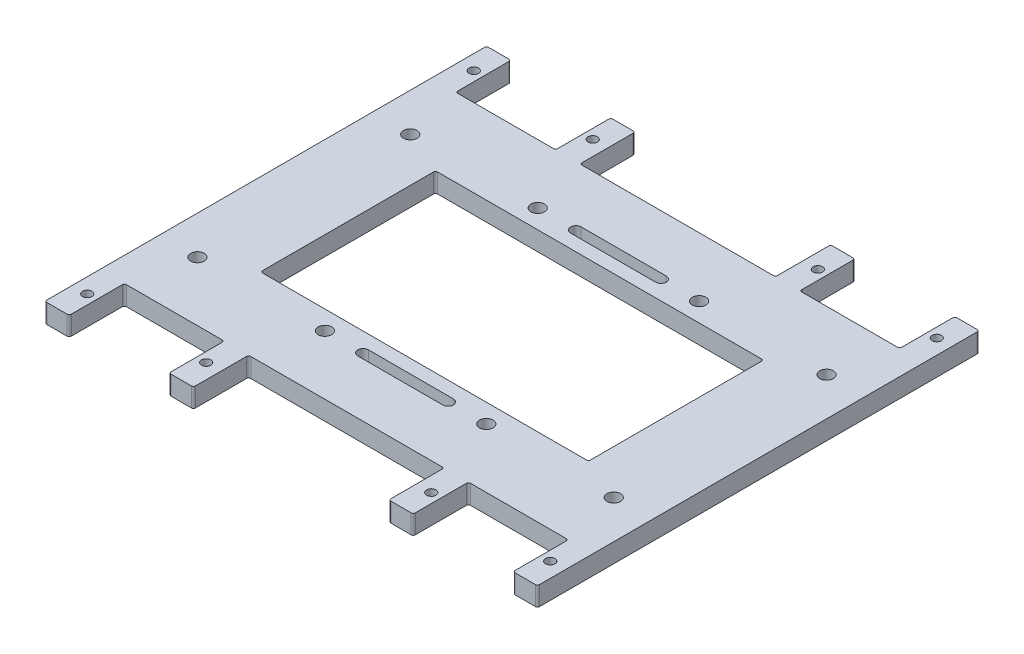
SolidWorks part; units mm, degrees
ref_plane "前视基准面" through (0, 0, 0) normal (0, 0, 1) x (1, 0, 0)
ref_plane "上视基准面" through (0, 0, 0) normal (0, 1, 0) x (1, 0, 0)
ref_plane "右视基准面" through (0, 0, 0) normal (1, 0, 0) x (0, 0, -1)
other "Configuration Table"
sketch "草图1" plane through (0, 0, 0) normal (0, 1, 0) x (1, 0, 0)
  line L0 (-58, -39) -> (-58, -52)
  line L2 (-58, 39) -> (-58, -39)
  line L4 (58, 39) -> (58, -39)
  line L5 (-58, 39) -> (58, -39) construction
  line L6 (-58, -39) -> (58, 39) construction
  line L15 (-78.7463, 0) -> (58.6748, 0) construction
  line L50 (-58, -52) -> (-52.25, -52)
  line L53 (-52.25, -52) -> (-52.25, -39)
  line L54 (-52.25, -39) -> (-28.75, -39)
  line L55 (-28.75, -39) -> (-28.75, -52)
  line L56 (-28.75, -52) -> (-23, -52)
  line L57 (-23, -52) -> (-23, -39)
  line L58 (-23, -39) -> (23, -39)
  line L59 (0, -1000) -> (0, 49000) construction
  line L60 (23, -52) -> (23, -39)
  line L61 (28.75, -52) -> (23, -52)
  line L62 (28.75, -39) -> (28.75, -52)
  line L63 (52.25, -39) -> (28.75, -39)
  line L64 (52.25, -52) -> (52.25, -39)
  line L65 (58, -52) -> (52.25, -52)
  line L66 (58, -39) -> (58, -52)
  line L67 (52.25, 39) -> (28.75, 39)
  line L68 (-23, 39) -> (23, 39)
  line L69 (-52.25, 39) -> (-28.75, 39)
  line L70 (0, 1000) -> (0, -49000) construction
  line L71 (58, 39) -> (58, 52)
  line L72 (58, 52) -> (52.25, 52)
  line L73 (52.25, 52) -> (52.25, 39)
  line L74 (28.75, 39) -> (28.75, 52)
  line L75 (28.75, 52) -> (23, 52)
  line L76 (23, 52) -> (23, 39)
  line L77 (-23, 52) -> (-23, 39)
  line L78 (-28.75, 52) -> (-23, 52)
  line L79 (-28.75, 39) -> (-28.75, 52)
  line L80 (-52.25, 52) -> (-52.25, 39)
  line L81 (-58, 52) -> (-52.25, 52)
  line L82 (-58, 39) -> (-58, 52)
  point P0 (0, 0)
  point P19 (0, -39)
  dimension "D8" = 23.5
  dimension "D10" = 23
  dimension "D2" = 78
  dimension "D3" = 13
  dimension "D4" = 13
  dimension "D5" = 13
  dimension "D6" = 13
  dimension "D7" = 5.75
  dimension "D9" = 5.75
extrude "凸台-拉伸1" add sketch "草图1" against normal blind 4.5
sketch "草图10" plane through (0, 0, 0) normal (0, 1, 0) x (1, 0, 0)
  line L5 (38.6, 20.6) -> (-38.6, 20.6)
  line L6 (38.6, 20.6) -> (38.6, -20.6)
  line L7 (38.6, -20.6) -> (-38.6, -20.6)
  line L8 (-38.6, 20.6) -> (-38.6, -20.6)
  line L9 (38.6, 20.6) -> (-38.6, -20.6) construction
  line L10 (38.6, -20.6) -> (-38.6, 20.6) construction
  point P0 (0, 0)
  dimension "D1" = 77.2
  dimension "D2" = 41.2
extrude "切除-拉伸5" cut sketch "草图10" against normal through all
sketch "草图16" plane through (0, 0, 0) normal (0, 1, 0) x (1, 0, 0)
  line L0 (-10, 25.05) -> (10, 25.05) construction
  line L1 (-10, 26.3) -> (10, 26.3)
  line L2 (-10, 23.8) -> (10, 23.8)
  line L3 (-1000, 0) -> (49000, 0) construction
  line L4 (0, -1000) -> (0, 49000) construction
  line L6 (-10, -25.05) -> (10, -25.05) construction
  line L7 (-10, -26.3) -> (10, -26.3)
  line L8 (-10, -23.8) -> (10, -23.8)
  arc A0 (-10, 26.3) -> (-10, 23.8) centre (-10, 25.05) ccw
  arc A1 (10, 23.8) -> (10, 26.3) centre (10, 25.05) ccw
  arc A2 (-10, -26.3) -> (-10, -23.8) centre (-10, -25.05) cw
  arc A3 (10, -23.8) -> (10, -26.3) centre (10, -25.05) cw
  circle A4 centre (19, 25.05) radius 1.6
  circle A5 centre (49, 25.05) radius 1.6
  circle A6 centre (-49, 25.05) radius 1.6
  circle A7 centre (-19, 25.05) radius 1.6
  circle A8 centre (49, -25.05) radius 1.6
  circle A9 centre (19, -25.05) radius 1.6
  circle A10 centre (-19, -25.05) radius 1.6
  circle A11 centre (-49, -25.05) radius 1.6
  point P2 (0, 25.05)
  point P17 (0, -25.05)
  dimension "D4" = 3.2
  dimension "D5" = 3.2
  dimension "D1" = 2.5
  dimension "D2" = 20
  dimension "D7" = 9
  dimension "D8" = 30
extrude "切除-拉伸6" cut sketch "草图16" against normal blind 10
sketch "草图17" plane through (0, 0, 0) normal (0, 1, 0) x (1, 0, 0)
  line L0 (-52.25, -39) -> (-28.75, -39) construction
  line L1 (-52.25, -52) -> (-52.25, -39) construction
  line L2 (-28.75, -39) -> (-28.75, -52) construction
  line L3 (-1000, 0) -> (49000, 0) construction
  line L4 (0, -1000) -> (0, 49000) construction
  circle A0 centre (-54.5, -45.5) radius 1.1
  circle A1 centre (-26.5, -45.5) radius 1.1
  circle A2 centre (26.5, -45.5) radius 1.1
  circle A3 centre (54.5, -45.5) radius 1.1
  circle A4 centre (54.5, 45.5) radius 1.1
  circle A5 centre (-26.5, 45.5) radius 1.1
  circle A6 centre (-54.5, 45.5) radius 1.1
  circle A7 centre (26.5, 45.5) radius 1.1
  point P21 (26.5, 45.5)
  dimension "D3" = 2.2
  dimension "D4" = 2.2
  dimension "D1" = 6.5
  dimension "D2" = 2.25
  dimension "D5" = 6.5
  dimension "D6" = 2.25
extrude "切除-拉伸7" cut sketch "草图17" against normal blind 10
fillet "圆角1" radius 0.5 32 edges at (52.25, -2.25, -39) (28.75, -2.25, -39) (23, -2.25, -39) (-23, -2.25, -39) (-28.75, -2.25, -39) (-52.25, -2.25, -39) (-52.25, -2.25, 52) (-52.25, -2.25, 39) (-28.75, -2.25, 39) (-28.75, -2.25, 52) (-23, -2.25, 52) (-23, -2.25, 39) (23, -2.25, 39) (23, -2.25, 52) (28.75, -2.25, 52) (28.75, -2.25, 39) (52.25, -2.25, 39) (52.25, -2.25, 52) (58, -2.25, 52) (-38.6, -2.25, -20.6) (38.6, -2.25, -20.6) (38.6, -2.25, 20.6) (-38.6, -2.25, 20.6) (-58, -2.25, 52) (58, -2.25, -52) (52.25, -2.25, -52) (28.75, -2.25, -52) (23, -2.25, -52) (-23, -2.25, -52) (-28.75, -2.25, -52) (-52.25, -2.25, -52) (-58, -2.25, -52)
sketch "草图14" plane through (0, -3, 0) normal (0, -1, 0) x (1, 0, 0)
  line L0 (4.73, 0) -> (-4.73, 0) construction
  line L1 (-42, 24) -> (-37, 24)
  line L2 (-42, 24) -> (-42, 20)
  line L3 (-42, 20) -> (-37, 20)
  line L4 (-37, 24) -> (-37, 20)
  line L5 (-42, 24) -> (-37, 20) construction
  line L6 (-42, 20) -> (-37, 24) construction
  line L7 (-42, -20) -> (-37, -20)
  line L8 (-37, -24) -> (-37, -20)
  line L9 (-42, -24) -> (-37, -24)
  line L10 (-42, -24) -> (-42, -20)
  line L11 (0, -4.73) -> (0, 4.73) construction
  line L12 (42, -24) -> (42, -20)
  line L13 (42, -24) -> (37, -24)
  line L14 (37, -24) -> (37, -20)
  line L15 (42, -20) -> (37, -20)
  line L16 (42, 20) -> (37, 20)
  line L17 (37, 24) -> (37, 20)
  line L18 (42, 24) -> (37, 24)
  line L19 (42, 24) -> (42, 20)
  point P0 (-39.5, 22)
  dimension "D1" = 22
  dimension "D2" = 5
  dimension "D3" = 4
sketch "草图15" plane through (0, -3, 0) normal (0, -1, 0) x (1, 0, 0)
  line L0 (-45, 23) -> (32, 23) construction
  line L1 (-41, 20) -> (41, 20)
  line L2 (-41, 20) -> (-41, 16)
  line L3 (-41, 16) -> (41, 16)
  line L4 (41, 20) -> (41, 16)
  line L5 (-41, 20) -> (41, 16) construction
  line L6 (-41, 16) -> (41, 20) construction
  line L7 (4.73, 0) -> (-4.73, 0) construction
  line L8 (-41, -16) -> (41, -16)
  line L9 (41, -20) -> (41, -16)
  line L10 (-41, -20) -> (41, -20)
  line L11 (-41, -20) -> (-41, -16)
  line L12 (0, -4.73) -> (0, 4.73) construction
  line L13 (-40.75, 10) -> (-38.25, 10)
  line L14 (-40.75, 10) -> (-40.75, -10)
  line L15 (-40.75, -10) -> (-38.25, -10)
  line L16 (-38.25, 10) -> (-38.25, -10)
  line L17 (-40.75, 10) -> (-38.25, -10) construction
  line L18 (-40.75, -10) -> (-38.25, 10) construction
  line L19 (40.75, -10) -> (38.25, -10)
  line L20 (38.25, 10) -> (38.25, -10)
  line L21 (40.75, 10) -> (38.25, 10)
  line L22 (40.75, 10) -> (40.75, -10)
  point P0 (0, 18)
  point P5 (-39.5, 0)
  dimension "D1" = 4
  dimension "D2" = 5
  dimension "D3" = 82
  dimension "D4" = 2.5
  dimension "D5" = 20
